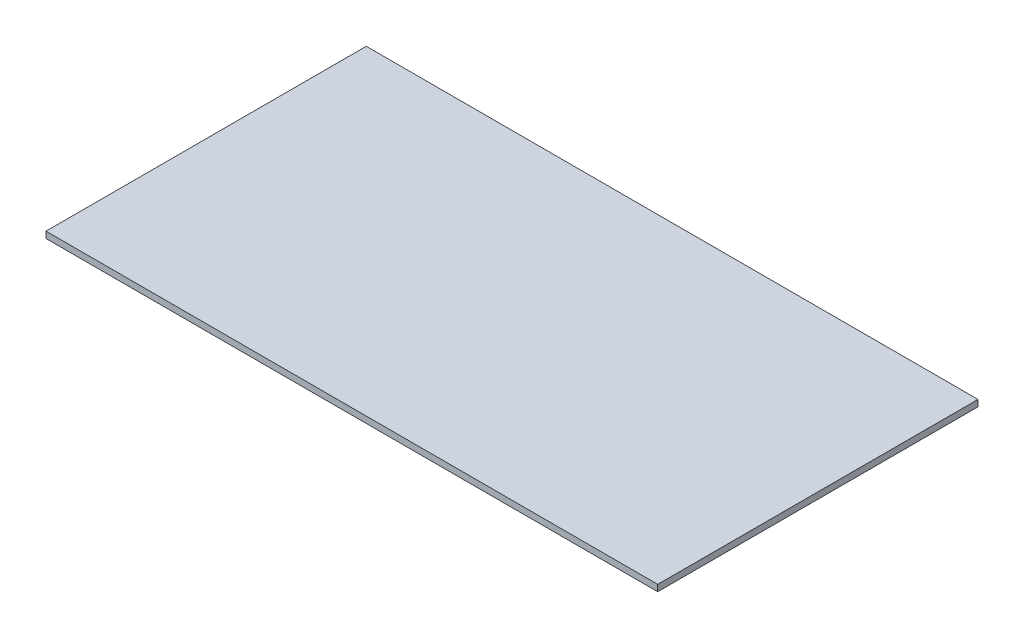
SolidWorks part; units mm, degrees
ref_plane "前视基准面" through (0, 0, 0) normal (0, 0, 1) x (1, 0, 0)
ref_plane "上视基准面" through (0, 0, 0) normal (0, 1, 0) x (1, 0, 0)
ref_plane "右视基准面" through (0, 0, 0) normal (1, 0, 0) x (0, 0, -1)
sketch "草图1" plane through (0, 0, 0) normal (0, 1, 0) x (1, 0, 0)
  line L1 (-53.3215, 25.6913) -> (137.6785, 25.6913)
  line L2 (-53.3215, 25.6913) -> (-53.3215, -74.3087)
  line L3 (-53.3215, -74.3087) -> (137.6785, -74.3087)
  line L4 (137.6785, 25.6913) -> (137.6785, -74.3087)
  dimension "D1" = 191
  dimension "D2" = 100
extrude "凸台-拉伸1" add sketch "草图1" along normal blind 2
